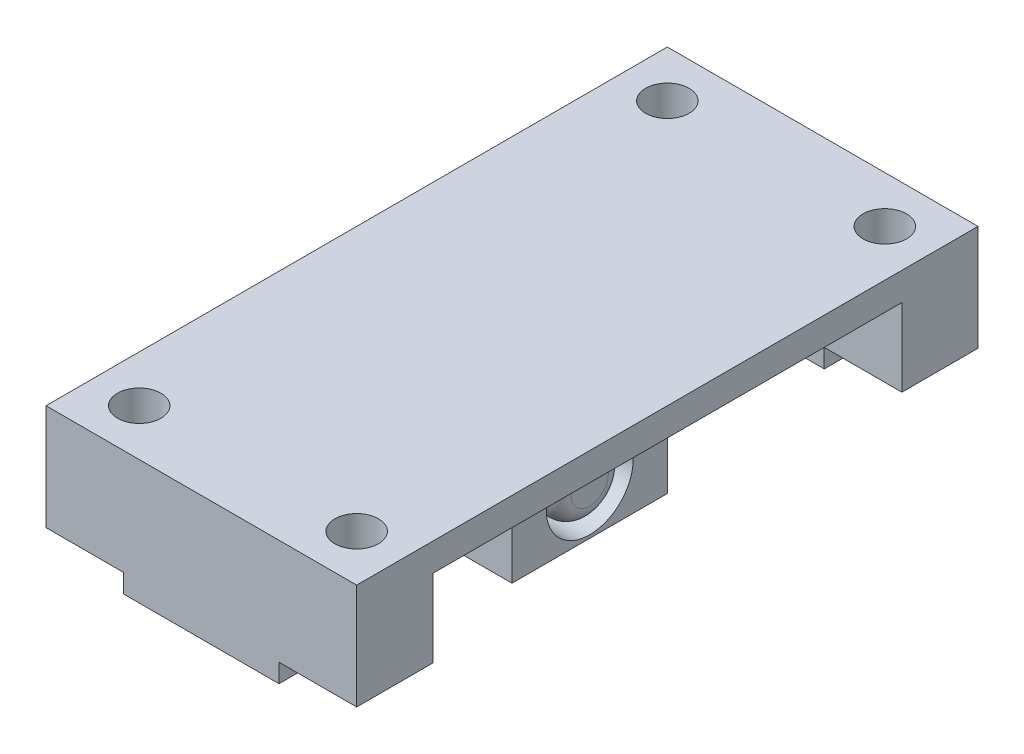
SolidWorks part; units mm, degrees
ref_plane "정면" through (0, 0, 0) normal (0, 0, 1) x (1, 0, 0)
ref_plane "윗면" through (0, 0, 0) normal (0, 1, 0) x (1, 0, 0)
ref_plane "우측면" through (0, 0, 0) normal (1, 0, 0) x (0, 0, -1)
sketch "스케치1" plane through (0, 0, 0) normal (1, 0, 0) x (0, 0, -1)
  line L0 (0, 0) -> (0, 6.8968) construction
  line L1 (20, 6.8968) -> (-20, 6.8968)
  line L2 (-20, 6.8968) -> (-20, -1.1032)
  line L3 (-20, -1.1032) -> (-15.1, -1.1032)
  line L4 (-15.1, -1.1032) -> (-15.1, 5.1)
  line L5 (-15.1, 5.1) -> (-5, 5.1)
  line L6 (-5, 5.1) -> (-5, -3)
  line L7 (-5, -3) -> (5, -3)
  line L8 (5, 5.1) -> (5, -3)
  line L9 (15.1, 5.1) -> (5, 5.1)
  line L10 (15.1, -1.1032) -> (15.1, 5.1)
  line L11 (20, -1.1032) -> (15.1, -1.1032)
  line L12 (20, 6.8968) -> (20, -1.1032)
  circle A0 centre (0, 0) radius 2
  point P12 (0, -3)
  dimension "D1" = 4
  dimension "D2" = 10
  dimension "D3" = 10.1
  dimension "D4" = 3
  dimension "D5" = 5.1
  dimension "D6" = 40
  dimension "D7" = 8
extrude "보스-돌출1" add sketch "스케치1" along normal mid plane 10
sketch "스케치3" plane through (0, 0, 0) normal (1, 0, 0) x (0, 0, -1)
  line L0 (20, -1.1032) -> (20, 6.8968) construction
  line L1 (-20, 6.8968) -> (20, 6.8968)
  line L2 (-20, 6.8968) -> (-20, 5.1)
  line L3 (-20, 5.1) -> (20, 5.1)
  line L4 (20, 6.8968) -> (20, 5.1)
  line L5 (-15.1, 5.1) -> (-5, 5.1) construction
extrude "보스-돌출2" add sketch "스케치3" along normal mid plane 20
sketch "스케치4" plane through (0, 0, 0) normal (0, 1, 0) x (1, 0, 0)
  line L0 (0, 0) -> (-13.0605, 0) construction
  line L1 (0, 0) -> (0, 18.7428) construction
  circle A0 centre (-7, -17) radius 1.4
  circle A1 centre (7, -17) radius 1.4
  circle A2 centre (7, 17) radius 1.4
  circle A3 centre (-7, 17) radius 1.4
  dimension "D1" = 2.8
  dimension "D2" = 17
  dimension "D3" = 7
extrude "컷-돌출2" cut sketch "스케치4" along normal blind 20
sketch "스케치6" plane through (5, 0, 0) normal (1, 0, 0) x (0, 0, -1)
  circle A0 centre (0, 0) radius 2.5
  dimension "D1" = 5
extrude "보스-돌출3" add sketch "스케치6" against normal blind 7
sketch "스케치7" plane through (5, 0, 0) normal (1, 0, 0) x (0, 0, -1)
  circle A0 centre (0, 0) radius 2.8
  circle A1 centre (0, 0) radius 2.2
  dimension "D1" = 5.6
  dimension "D2" = 4.4
extrude "컷-돌출3" cut sketch "스케치7" against normal blind 5
fillet "필렛1" radius 1 1 edges at (5, 0, -2.2)
sketch "스케치8" plane through (0, 5.1, 0) normal (0, -1, 0) x (1, 0, 0)
  line L0 (-5, -15.1) -> (-5, -20) construction
  line L1 (-5, 15.1) -> (-10, 15.1)
  line L2 (-5, 15.1) -> (-5, 20)
  line L3 (-5, 20) -> (-10, 20)
  line L4 (-10, 15.1) -> (-10, 20)
  line L5 (5, 15.1) -> (10, 15.1)
  line L6 (5, 15.1) -> (5, 20)
  line L7 (5, 20) -> (10, 20)
  line L8 (10, 15.1) -> (10, 20)
  line L9 (-10, -20) -> (-5, -20)
  line L10 (-10, -20) -> (-10, -15.1)
  line L11 (-10, -15.1) -> (-5, -15.1)
  line L12 (-5, -20) -> (-5, -15.1)
  line L13 (5, -15.1) -> (-5, -15.1) construction
  line L15 (10, -20) -> (5, -20)
  line L16 (10, -20) -> (10, -15.1)
  line L17 (10, -15.1) -> (5, -15.1)
  line L18 (5, -20) -> (5, -15.1)
  circle A0 centre (-7, -17) radius 1.4
  circle A1 centre (7, -17) radius 1.4
  circle A2 centre (7, 17) radius 1.4
  circle A3 centre (-7, 17) radius 1.4
extrude "보스-돌출4" add sketch "스케치8" along normal blind 5
